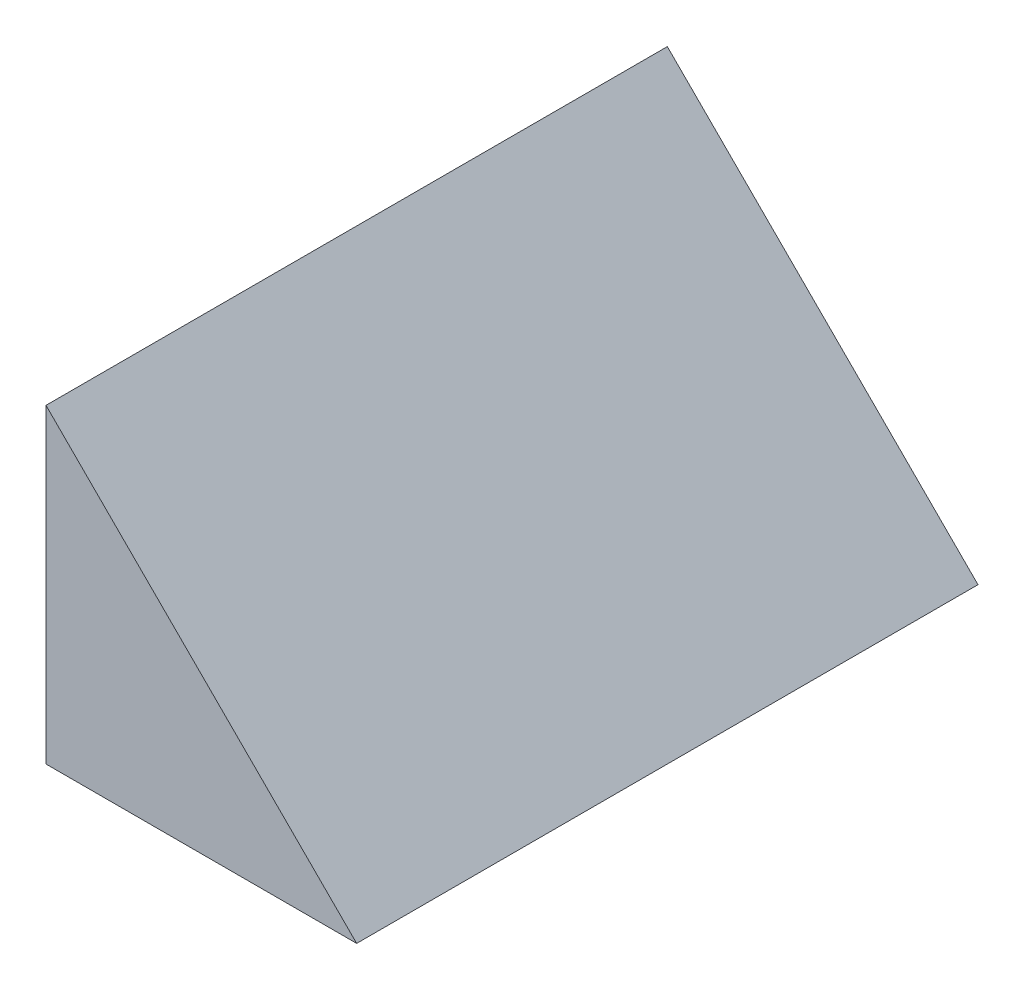
SolidWorks part; units mm, degrees
material "Balsa"
ref_plane "Front Plane" through (0, 0, 0) normal (0, 0, 1) x (1, 0, 0)
ref_plane "Top Plane" through (0, 0, 0) normal (0, 1, 0) x (1, 0, 0)
ref_plane "Right Plane" through (0, 0, 0) normal (1, 0, 0) x (0, 0, -1)
sketch "Sketch1" plane through (0, 0, 0) normal (0, 0, 1) x (1, 0, 0)
  line L0 (0, 0) -> (6.35, 0)
  line L1 (6.35, 0) -> (0, 6.35)
  line L2 (0, 6.35) -> (0, 0)
extrude "Boss-Extrude1" add sketch "Sketch1" along normal blind 12.7
